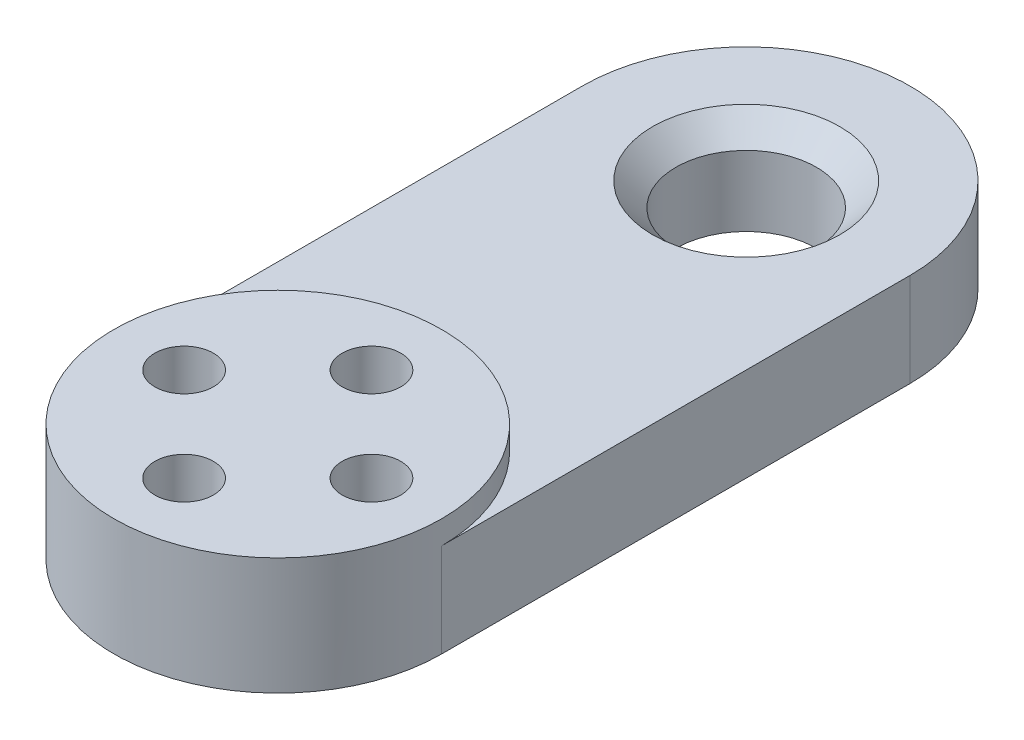
SolidWorks part; units mm, degrees
material "Thornel Mat VMA"
ref_plane "前视基准面" through (0, 0, 0) normal (0, 0, 1) x (1, 0, 0)
ref_plane "上视基准面" through (0, 0, 0) normal (0, 1, 0) x (1, 0, 0)
ref_plane "右视基准面" through (0, 0, 0) normal (1, 0, 0) x (0, 0, -1)
other "Configuration Table"
sketch "草图1" plane through (0, 0, 0) normal (0, 1, 0) x (1, 0, 0)
  line L0 (-7, 0) -> (-7, 20)
  line L1 (7, 20) -> (7, 0)
  circle A0 centre (0, 0) radius 4 construction
  arc A1 (-7, 0) -> (7, 0) centre (0, 0) ccw
  circle A2 centre (0, 4) radius 1.25
  circle A3 centre (4, 0) radius 1.25
  circle A4 centre (0, -4) radius 1.25
  circle A5 centre (-4, 0) radius 1.25
  arc A6 (7, 20) -> (-7, 20) centre (0, 20) ccw
  circle A7 centre (0, 20) radius 3
  point P15 (0, 0)
  dimension "D1" = 8
  dimension "D2" = 2.5
  dimension "D4" = 14
  dimension "D6" = 14
  dimension "D7" = 6
  dimension "D5" = 20
  dimension "D3" = 4
extrude "凸台-拉伸1" add sketch "草图1" along normal blind 4
chamfer "倒角1" distance 1 angle 45 1 edges at (0, 4, -17)
sketch "草图2" plane through (0, 4, 0) normal (0, 1, 0) x (1, 0, 0)
  circle A0 centre (0, 0) radius 7
  circle A1 centre (0, 0) radius 4 construction
  circle A2 centre (4, 0) radius 1.25
  circle A3 centre (0, 4) radius 1.25
  circle A4 centre (-4, 0) radius 1.25
  circle A5 centre (0, -4) radius 1.25
  dimension "D1" = 14
  dimension "D2" = 2.5
extrude "凸台-拉伸2" add sketch "草图2" along normal blind 1
